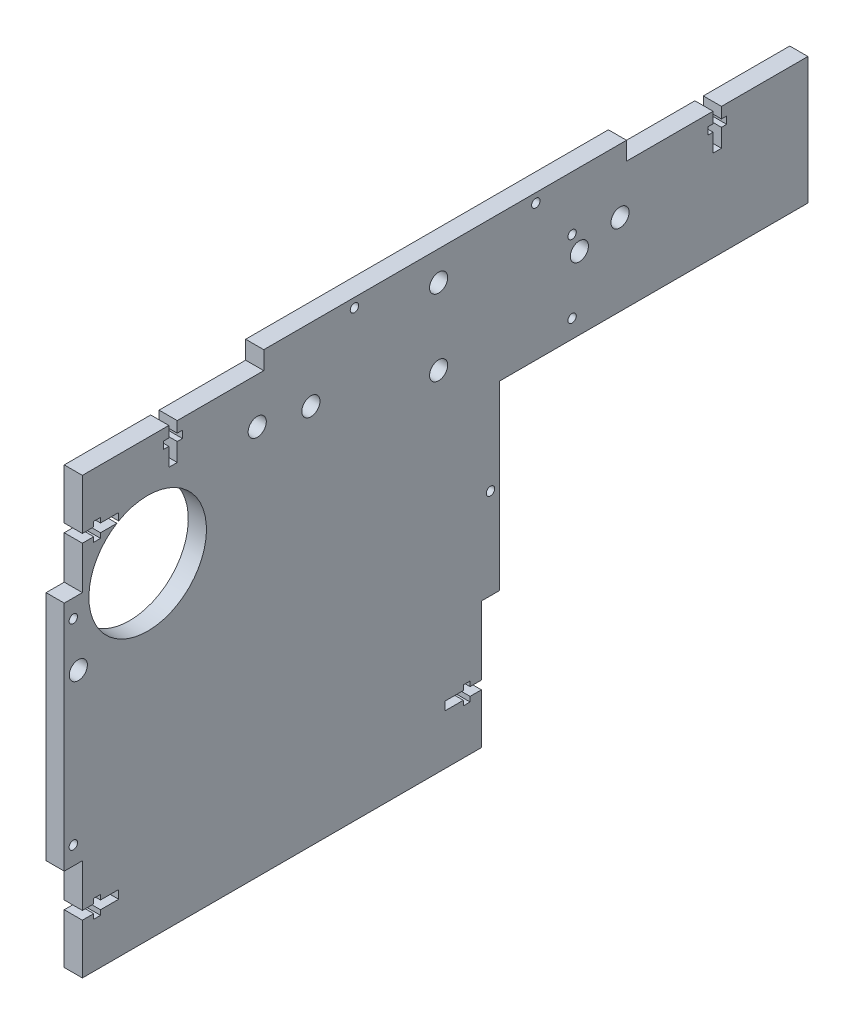
SolidWorks part; units mm, degrees
material "Acrylic (Medium-high impact)"
ref_plane "Front Plane" through (0, 0, 0) normal (0, 0, 1) x (1, 0, 0)
ref_plane "Top Plane" through (0, 0, 0) normal (0, 1, 0) x (1, 0, 0)
ref_plane "Right Plane" through (0, 0, 0) normal (1, 0, 0) x (0, 0, -1)
sketch "Sketch1" plane through (0, 0, 0) normal (1, 0, 0) x (0, 0, -1)
  line L0 (63.5, 158.75) -> (139.7, 158.75)
  line L1 (0, 0) -> (139.7, 0)
  line L2 (0, 0) -> (0, 152.4)
  line L4 (139.7, 0) -> (139.7, 107.95)
  line L7 (0, 152.4) -> (63.5, 152.4)
  line L9 (63.5, 158.75) -> (63.5, 152.4)
  line L10 (139.7, 158.75) -> (190.5, 158.75)
  line L11 (190.5, 158.75) -> (190.5, 152.4)
  line L12 (190.5, 152.4) -> (254, 152.4)
  line L13 (254, 152.4) -> (254, 107.95)
  line L14 (254, 107.95) -> (139.7, 107.95)
  dimension "D1" = 158.75
  dimension "D2" = 139.7
  dimension "D3" = 6.35
  dimension "D4" = 63.5
  dimension "D5" = 127
  dimension "D6" = 63.5
  dimension "D7" = 44.45
  dimension "D8" = 6.35
  dimension "D9" = 152.4
extrude "Boss-Extrude1" add sketch "Sketch1" along normal blind 6.35
sketch "Sketch2" plane through (0, 0, 0) normal (-1, 0, 0) x (0, 0, 1)
  line L0 (0, 152.4) -> (0, 0) construction
  line L1 (0, 17.526) -> (-3.9687, 17.526)
  line L2 (0, 17.526) -> (0, 20.4724)
  line L3 (0, 20.4724) -> (-3.9687, 20.4724)
  line L4 (-12.7, 17.526) -> (-12.7, 20.4724)
  line L6 (-6.35, 17.526) -> (-12.7, 17.526)
  line L7 (-3.9687, 15.8242) -> (-6.35, 15.8242)
  line L8 (-3.9687, 15.8242) -> (-3.9687, 17.526)
  line L9 (-3.9688, 22.1742) -> (-6.35, 22.1742)
  line L10 (-6.35, 15.8242) -> (-6.35, 17.526)
  line L11 (-3.9687, 20.4724) -> (-3.9688, 22.1742)
  line L12 (-6.35, 20.4724) -> (-6.35, 22.1742)
  line L13 (-6.35, 20.4724) -> (-12.7, 20.4724)
  line L14 (-69.85, 189.7453) -> (-69.85, -47.9109) construction
  line L16 (0, 0) -> (-139.7, 0) construction
  line L18 (-139.7, 17.526) -> (-139.7, 20.4724)
  line L19 (-127, 17.526) -> (-127, 20.4724)
  line L20 (-135.7312, 15.8242) -> (-135.7312, 17.526)
  line L21 (-133.35, 15.8242) -> (-133.35, 17.526)
  line L22 (-135.7313, 20.4724) -> (-135.7313, 22.1742)
  line L23 (-133.35, 20.4724) -> (-133.35, 22.1742)
  line L24 (-135.7313, 22.1742) -> (-133.35, 22.1742)
  line L25 (-135.7312, 15.8242) -> (-133.35, 15.8242)
  line L26 (-139.7, 17.526) -> (-135.7312, 17.526)
  line L27 (-139.7, 20.4724) -> (-135.7313, 20.4724)
  line L28 (-133.35, 20.4724) -> (-127, 20.4724)
  line L29 (-133.35, 17.526) -> (-127, 17.526)
  line L42 (-12.7, 134.7724) -> (-12.7, 131.826)
  line L43 (-6.35, 131.826) -> (-12.7, 131.826)
  line L44 (-6.35, 134.7724) -> (-12.7, 134.7724)
  line L45 (-6.35, 136.4742) -> (-6.35, 134.7724)
  line L46 (-3.9688, 136.4742) -> (-6.35, 136.4742)
  line L47 (-3.9688, 136.4742) -> (-3.9688, 134.7724)
  line L48 (-6.35, 131.826) -> (-6.35, 130.1242)
  line L49 (-3.9688, 130.1242) -> (-6.35, 130.1242)
  line L50 (-3.9688, 131.826) -> (-3.9688, 130.1242)
  line L51 (0, 131.826) -> (-3.9688, 131.826)
  line L52 (0, 134.7724) -> (-3.9688, 134.7724)
  line L53 (0, 134.7724) -> (0, 131.826)
  line L54 (0, 17.526) -> (6.35, 17.526) construction
  line L62 (0, 131.826) -> (6.35, 131.826) construction
  line L71 (0, 116.84) -> (0, 152.4) construction
  point P9 (-6.35, 135.6233)
  point P23 (-69.85, 0)
  dimension "D1" = 2.9464
  dimension "D2" = 12.7
  dimension "D3" = 6.35
  dimension "D4" = 6.35
  dimension "D5" = 2.3813
  dimension "D6" = 2.9464
  dimension "D7" = 6.35
  dimension "D8" = 2.3813
  dimension "D9" = 12.7
  dimension "D10" = 6.35
extrude "Cut-Extrude1" cut sketch "Sketch2" against normal through all
sketch "Sketch4" plane through (0, 0, 0) normal (-1, 0, 0) x (0, 0, 1)
  line L0 (0, 131.826) -> (0, 20.4724) construction
  line L1 (0, 35.56) -> (6.35, 35.56)
  line L2 (0, 35.56) -> (0, 116.84)
  line L3 (0, 116.84) -> (6.35, 116.84)
  line L4 (6.35, 35.56) -> (6.35, 116.84)
  line L5 (-139.7, 44.45) -> (-146.05, 44.45) construction
  line L7 (-139.7, 107.95) -> (-254, 107.95) construction
  line L8 (-139.7, 107.95) -> (-146.05, 107.95)
  line L9 (-146.05, 44.45) -> (-146.05, 107.95)
  line L10 (-139.7, 44.45) -> (-146.05, 44.45)
  line L11 (-139.7, 44.45) -> (-139.7, 107.95)
  line L12 (0, 116.84) -> (6.35, 116.84) construction
  line L16 (0, 35.56) -> (6.35, 35.56) construction
  line L17 (6.35, 116.84) -> (6.35, 152.4) construction
  line L19 (-146.05, 44.45) -> (-146.05, 0) construction
  line L20 (-139.7, 44.45) -> (-139.7, 0) construction
extrude "Boss-Extrude3" add sketch "Sketch4" against normal up to surface (6.35 mm away)
sketch "Sketch5" plane through (0, 0, 0) normal (-1, 0, 0) x (0, 0, 1)
  line L0 (6.35, 35.56) -> (6.35, 116.84) construction
  line L1 (-146.05, 107.95) -> (-146.05, 44.45) construction
  line L3 (6.35, 76.2) -> (-44.9947, 76.2) construction
  line L4 (6.35, 35.56) -> (6.35, 116.84) construction
  line L5 (0, 35.56) -> (6.35, 35.56) construction
  circle A1 centre (3.175, 41.91) radius 1.4732
  circle A2 centre (-142.875, 76.2) radius 1.4732
  circle A3 centre (3.175, 110.49) radius 1.4732
  point P5 (-146.05, 76.2)
  point P11 (6.35, 76.2)
  dimension "D1" = 2.9464
  dimension "D2" = 3.175
  dimension "D3" = 2.9464
  dimension "D4" = 3.175
  dimension "D5" = 6.35
extrude "Cut-Extrude2" cut sketch "Sketch5" against normal through all
sketch "Sketch6" plane through (0, 0, 0) normal (-1, 0, 0) x (0, 0, 1)
  line L0 (-63.5, 152.4) -> (0, 152.4) construction
  line L1 (-30.2641, 152.4) -> (-33.2105, 152.4)
  line L2 (-30.2641, 152.4) -> (-30.2641, 148.59)
  line L3 (-30.2641, 139.7) -> (-33.2105, 139.7)
  line L4 (-33.2105, 152.4) -> (-33.2105, 148.59)
  line L5 (-33.2105, 146.05) -> (-33.2105, 139.7)
  line L6 (-28.4353, 146.05) -> (-30.2641, 146.05)
  line L7 (-28.4353, 146.05) -> (-28.4353, 148.59)
  line L8 (-28.4353, 148.59) -> (-30.2641, 148.59)
  line L9 (-35.0393, 146.05) -> (-35.0393, 148.59)
  line L10 (-33.2105, 146.05) -> (-35.0393, 146.05)
  line L11 (-30.2641, 146.05) -> (-30.2641, 139.7)
  line L12 (-33.2105, 148.59) -> (-35.0393, 148.59)
  line L16 (-33.2105, 158.75) -> (-33.2105, 152.4) construction
  line L17 (-254, 152.4) -> (-190.5, 152.4) construction
  line L18 (-220.7895, 152.4) -> (-223.7359, 152.4)
  line L19 (-220.7895, 152.4) -> (-220.7895, 148.59)
  line L20 (-220.7895, 139.7) -> (-223.7359, 139.7)
  line L21 (-223.7359, 152.4) -> (-223.7359, 148.59)
  line L22 (-190.5, 158.75) -> (-63.5, 158.75) construction
  line L23 (-218.9607, 146.05) -> (-220.7895, 146.05)
  line L24 (-218.9607, 146.05) -> (-218.9607, 148.59)
  line L25 (-218.9607, 148.59) -> (-220.7895, 148.59)
  line L26 (-225.5647, 146.05) -> (-225.5647, 148.59)
  line L29 (-223.7359, 148.59) -> (-225.5647, 148.59)
  line L30 (-220.7895, 146.05) -> (-220.7895, 139.7)
  line L31 (-223.7359, 146.05) -> (-225.5647, 146.05)
  line L32 (-223.7359, 146.05) -> (-223.7359, 139.7)
  line L42 (-220.7895, 152.4) -> (-220.7895, 158.75) construction
  circle A0 centre (-61.214, 136.5038) radius 3.175
  circle A1 centre (-80.01, 133.35) radius 3.175
  circle A2 centre (-95.25, 155.575) radius 1.4732
  circle A3 centre (-158.75, 155.575) radius 1.4732
  circle A4 centre (-188.224, 136.5038) radius 3.175
  circle A5 centre (-173.99, 133.35) radius 3.175
  circle A6 centre (-124.719, 148.4768) radius 3.175
  circle A7 centre (-124.719, 121.8988) radius 3.175
  circle A9 centre (-61.214, 136.5038) radius 3.175 construction
  circle A10 centre (-95.25, 155.575) radius 3.9624 construction
  circle A11 centre (-80.01, 133.35) radius 4.5244 construction
  circle A12 centre (-124.719, 121.8988) radius 3.175 construction
  circle A13 centre (-124.719, 148.4768) radius 3.175 construction
  circle A14 centre (-158.75, 155.575) radius 3.9624 construction
  circle A15 centre (-188.224, 136.5038) radius 3.175 construction
  point P51 (-222.2627, 152.4)
  dimension "D5" = 6.35
  dimension "D7" = 6.35
  dimension "D11" = 2.9464
  dimension "D14" = 2.9464
  dimension "D17" = 6.35
  dimension "D18" = 6.35
  dimension "D27" = 6.35
  dimension "D28" = 6.35
  dimension "D1" = 2.54
  dimension "D2" = 2.9464
  dimension "D3" = 6.604
  dimension "D4" = 12.7
  dimension "D6" = 6.35
  dimension "D20" = 25.4
  dimension "D22" = 12.7
  dimension "D23" = 2.9464
  dimension "D24" = 6.604
  dimension "D25" = 2.54
  dimension "D26" = 6.35
extrude "Cut-Extrude3" cut sketch "Sketch6" against normal through all
sketch "Sketch7" plane through (6.35, 0, 0) normal (1, 0, 0) x (0, 0, -1)
  circle A0 centre (-1.4195, 94.0611) radius 3.1764
  dimension "D1" = 6.3528
extrude "Cut-Extrude4" cut sketch "Sketch7" against normal up to next
sketch "Sketch8" plane through (0, 0, 0) normal (-1, 0, 0) x (0, 0, 1)
  line L0 (-146.05, 107.95) -> (-146.05, 44.45) construction
  line L1 (-220.7895, 152.4) -> (-190.5, 152.4) construction
  circle A0 centre (-171.45, 114.3) radius 1.4605
  circle A1 centre (-171.45, 139.7) radius 1.4605
  dimension "D1" = 2.921
  dimension "D2" = 2.921
  dimension "D3" = 25.4
  dimension "D4" = 25.4
  dimension "D5" = 12.7
  dimension "D6" = 25.4
extrude "Cut-Extrude5" cut sketch "Sketch8" against normal through all
sketch "Sketch11" plane through (0, 0, 0) normal (-1, 0, 0) x (0, 0, 1)
  line L1 (6.35, 35.56) -> (6.35, 116.84) construction
  line L2 (-30.2641, 152.4) -> (0, 152.4) construction
  circle A0 centre (-22.86, 114.3) radius 20.574
  dimension "D1" = 41.148
  dimension "D2" = 29.21
  dimension "D3" = 38.1
extrude "Cut-Extrude6" cut sketch "Sketch11" against normal blind 25.4
